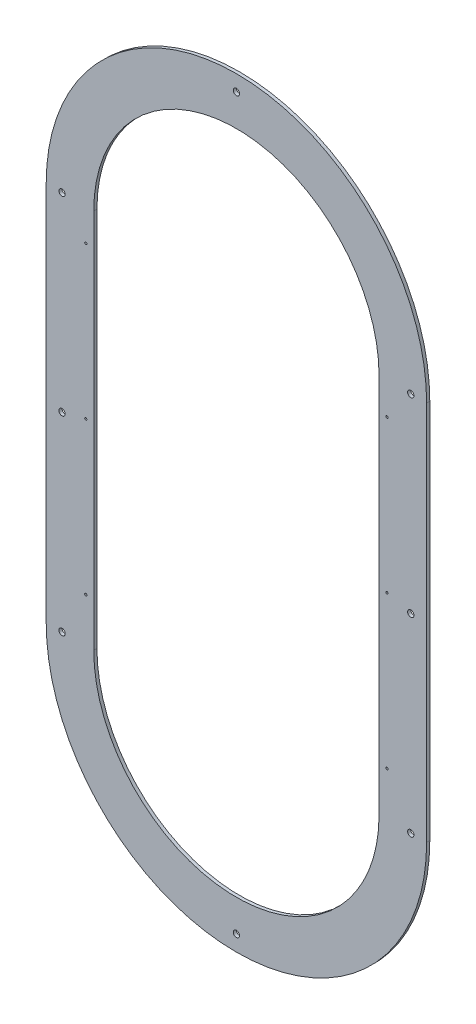
SolidWorks part; units mm, degrees
material "2024-O"
ref_plane "Front Plane" through (0, 0, 0) normal (0, 0, 1) x (1, 0, 0)
ref_plane "Top Plane" through (0, 0, 0) normal (0, 1, 0) x (1, 0, 0)
ref_plane "Right Plane" through (0, 0, 0) normal (1, 0, 0) x (0, 0, -1)
sketch "Sketch1" plane through (0, 0, 0) normal (0, 0, 1) x (1, 0, 0)
  line L0 (450, -600) -> (450, 600)
  line L2 (600, -600) -> (600, 600)
  line L4 (-600, -600) -> (-600, 600)
  line L5 (600, -600) -> (-600, 600) construction
  line L6 (600, 600) -> (-600, -600) construction
  line L7 (-450, -600) -> (-450, 600)
  line L8 (-550, -600) -> (-550, 600) construction
  line L9 (550, -600) -> (550, 600) construction
  line L10 (-550, 600) -> (-550, 0) construction
  line L11 (-550, 600) -> (-475, 600) construction
  line L12 (-550, 0) -> (-475, 0) construction
  line L18 (-475, 600) -> (0, 600) construction
  line L20 (0, 0) -> (0, 50000) construction
  line L21 (0, 0) -> (-50000, 0) construction
  arc A0 (-600, -600) -> (600, -600) centre (0, -600) ccw
  arc A1 (600, 600) -> (-600, 600) centre (0, 600) ccw
  arc A2 (450, 600) -> (-450, 600) centre (0, 600) ccw
  arc A3 (-450, -600) -> (450, -600) centre (0, -600) ccw
  arc A4 (550, 600) -> (-550, 600) centre (0, 600) ccw construction
  arc A5 (-550, -600) -> (550, -600) centre (0, -600) ccw construction
  circle A6 centre (0, 1150) radius 10
  circle A7 centre (-550, 600) radius 10
  circle A8 centre (-550, 0) radius 10
  circle A9 centre (-550, -600) radius 10
  circle A10 centre (550, 600) radius 10
  circle A11 centre (550, 0) radius 10
  circle A12 centre (550, -600) radius 10
  circle A13 centre (0, -1150) radius 10
  point P0 (0, 0)
  dimension "D3" = 150
  dimension "D5" = 20
  dimension "D1" = 1200
  dimension "D2" = 1200
  dimension "D6" = 75
  dimension "D4" = 50
extrude "Boss-Extrude1" add sketch "Sketch1" against normal blind 10
ref_plane "Plane1" through (0, 0, -10) normal (0, 0, 1) x (1, 0, 0)
ref_plane "Plane2" through (0, 0, -310) normal (0, 0, 1) x (1, 0, 0)
sketch "Sketch4" plane through (0, 0, -10) normal (0, 0, 1) x (1, 0, 0)
  line L2 (450, -600) -> (450, 600)
  line L4 (-450, -600) -> (-450, 600)
  line L5 (450, -600) -> (-450, 600) construction
  line L6 (450, 600) -> (-450, -600) construction
  line L12 (-500, -600) -> (-500, 600)
  line L13 (500, -600) -> (500, 600)
  arc A0 (-450, 600) -> (450, 600) centre (0, 600) cw
  arc A1 (-450, -600) -> (450, -600) centre (0, -600) ccw
  arc A8 (-500, 600) -> (500, 600) centre (0, 600) cw
  arc A9 (-500, -600) -> (500, -600) centre (0, -600) ccw
  point P0 (0, 0)
  dimension "D1" = 1200
  dimension "D2" = 900
  dimension "D3" = 50
sketch "Sketch5" plane through (0, 0, -310) normal (0, 0, 1) x (1, 0, 0)
  line L0 (450, -600) -> (450, 600) construction
  line L1 (-450, -600) -> (-450, 600)
  line L2 (450, -600) -> (-450, 600) construction
  line L3 (450, 600) -> (-450, -600) construction
  line L4 (1000, -1050) -> (-1000, -1050) construction
  line L5 (405.6157, -1200) -> (-405.6157, -1200)
  line L6 (-898.2325, -614.3925) -> (-591.1402, 1152.729)
  line L7 (0, 1050) -> (0, -1200) construction
  line L8 (898.2325, -614.3925) -> (591.1402, 1152.729)
  line L9 (1000, -1200) -> (-1000, -1200) construction
  line L10 (-750.4474, -640.0748) -> (-443.3552, 1127.0467)
  line L11 (750.4474, -640.0748) -> (443.3552, 1127.0467)
  line L12 (405.6157, -1050) -> (-405.6157, -1050)
  arc A0 (-450, 600) -> (450, 600) centre (0, 600) cw
  arc A1 (-450, -600) -> (450, -600) centre (0, -600) ccw
  arc A2 (591.1402, 1152.729) -> (-591.1402, 1152.729) centre (0, 1050) ccw
  arc A4 (405.6157, -1200) -> (898.2325, -614.3925) centre (405.6157, -700) ccw
  arc A5 (-405.6157, -1200) -> (-898.2325, -614.3925) centre (-405.6157, -700) cw
  arc A6 (443.3552, 1127.0467) -> (-443.3552, 1127.0467) centre (0, 1050) ccw
  arc A7 (405.6157, -1050) -> (750.4474, -640.0748) centre (405.6157, -700) ccw
  arc A8 (-405.6157, -1050) -> (-750.4474, -640.0748) centre (-405.6157, -700) cw
  point P0 (0, 0)
  point P12 (0, -1050)
  point P13 (0, -1050)
  point P20 (1000, -1200)
  dimension "D1" = 1200
  dimension "D4" = 500
  dimension "D2" = 2000
  dimension "D3" = 150
  dimension "D5" = 150
sketch "Furos de ligação" plane through (0, 0, -10) normal (0, 0, -1) x (-1, 0, 0)
  line L2 (0, 0) -> (0, 50000) construction
  line L8 (0, 600) -> (-475, 600) construction
  line L9 (0, 600) -> (-335.8757, 935.8757) construction
  line L10 (475, -600) -> (475, 600)
  line L11 (-475, 600) -> (-475, -600)
  line L12 (475, -600) -> (475, 600) construction
  line L13 (-475, 600) -> (-475, -600) construction
  line L14 (-475, -600) -> (0, -600) construction
  line L15 (0, -600) -> (-335.8757, -935.8757) construction
  circle A0 centre (-475, -300) radius 10
  circle A1 centre (-475, 300) radius 10
  circle A4 centre (-335.8757, 935.8757) radius 10
  circle A5 centre (-335.8757, -935.8757) radius 10
  circle A14 centre (335.8757, -935.8757) radius 10
  circle A15 centre (475, -300) radius 10
  arc A16 (475, 600) -> (-475, 600) centre (0, 600) ccw
  arc A17 (-475, -600) -> (475, -600) centre (0, -600) ccw
  arc A18 (475, 600) -> (-475, 600) centre (0, 600) ccw construction
  arc A19 (-475, -600) -> (475, -600) centre (0, -600) ccw construction
  circle A20 centre (475, 300) radius 10
  circle A21 centre (335.8757, 935.8757) radius 10
  dimension "D1" = 25
  dimension "D2" = 45
  dimension "D3" = 45
sketch "Sketch10" plane through (0, 0, -10) normal (0, 0, -1) x (-1, 0, 0)
  circle A0 centre (-475, 19.25) radius 3 construction
  circle A1 centre (-475, 19.25) radius 3
  circle A2 centre (-475, -460.75) radius 3 construction
  circle A3 centre (-475, 499.25) radius 3 construction
  circle A4 centre (-475, -460.75) radius 3
  circle A5 centre (-475, 499.25) radius 3
hole_wizard "Hole2" positions "3DSketch2" profile "Sketch11" legacy
sketch3d "3DSketch2"
  point P0 (475, 19.25, -10)
  point P3 (475, 499.25, -10)
  point P6 (475, -460.75, -10)
sketch "Sketch11" plane through (475, 19.25, -10) normal (1, 0, 0) x (0, 1, 0)
  line L0 (0, 0) -> (0, 10)
  line L1 (0, 10) -> (3.5, 10)
  line L2 (3.5, 10) -> (3.5, 5)
  line L3 (3.5, 5) -> (5, 5)
  line L4 (5, 5) -> (5, 0)
  line L5 (5, 0) -> (0, 0)
  line L6 (0, 110) -> (0, -10) construction
  dimension "Diameter" = 7
  dimension "Depth" = 10
  dimension "C-Bore Diameter" = 10
  dimension "C-Bore Depth" = 5
mirror "Mirror1" about plane through (0, 0, 0) normal (1, 0, 0) of "Hole2"
